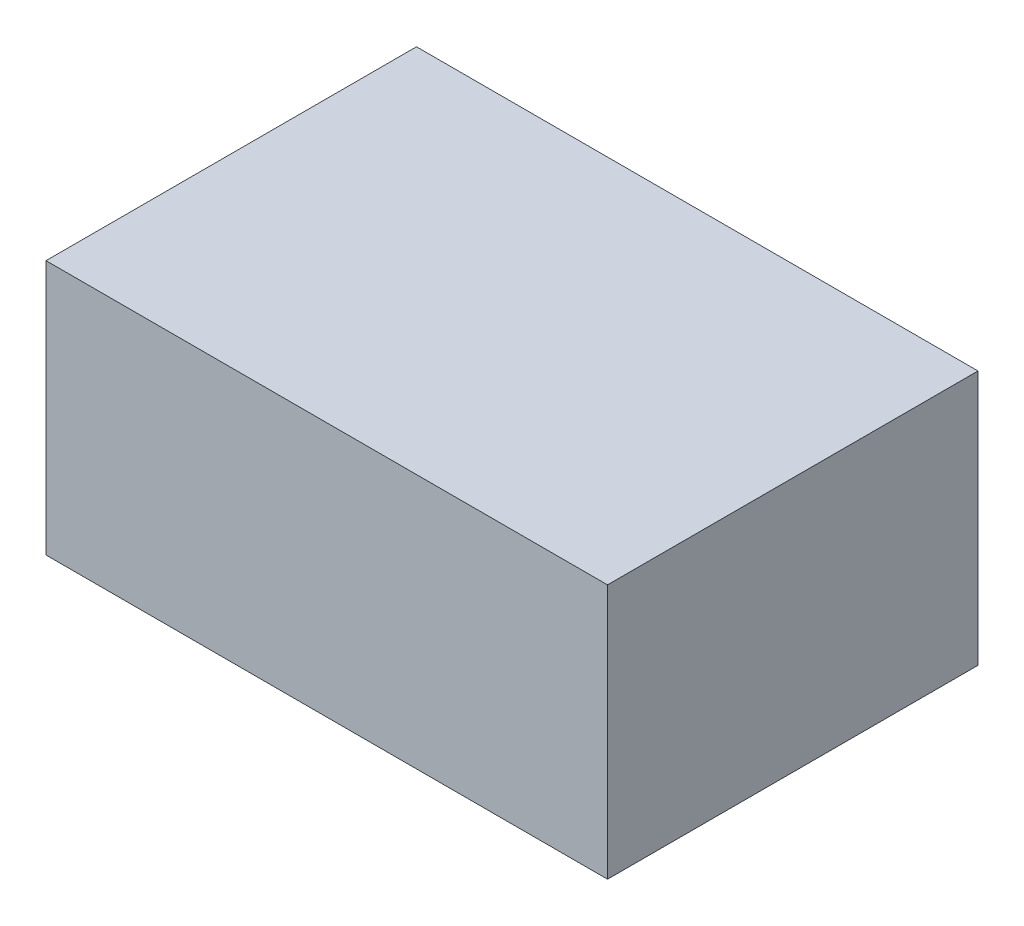
SolidWorks part; units mm, degrees
ref_plane "Front Plane" through (0, 0, 0) normal (0, 0, 1) x (1, 0, 0)
ref_plane "Top Plane" through (0, 0, 0) normal (0, 1, 0) x (1, 0, 0)
ref_plane "Right Plane" through (0, 0, 0) normal (1, 0, 0) x (0, 0, -1)
sketch "Sketch1" plane through (0, 94.8439, 0) normal (0, -1, 0) x (1, 0, 0)
  line L0 (462.1825, -188.3959) -> (474.7825, -157.5959) construction
  line L1 (474.7825, -157.5959) -> (474.7825, -189.4402) construction
  line L2 (474.7825, -189.4402) -> (462.1825, -157.5959) construction
  line L3 (468.4825, -188.3959) -> (468.4825, -157.5959) construction
  line L8 (443.5182, -157.3077) -> (493.7134, -189.5034) construction
  line L9 (443.7134, -189.5034) -> (493.5093, -156.6937) construction
  line L10 (474.7825, -188.3959) -> (462.1825, -188.3959) construction
  line L11 (462.1825, -157.5959) -> (474.7825, -157.5959) construction
  line L13 (443.4825, -153.1828) -> (493.4825, -153.1828)
  line L14 (443.4825, -153.1828) -> (443.4825, -186.171)
  line L15 (443.4825, -186.171) -> (493.4825, -186.171)
  line L16 (493.4825, -153.1828) -> (493.4825, -186.171)
  line L17 (443.4825, -153.1828) -> (493.4825, -186.171) construction
  line L18 (443.4825, -186.171) -> (493.4825, -153.1828) construction
  point P4 (468.3774, -173.2527)
  point P19 (468.4825, -169.6769)
  dimension "D1" = 50
  dimension "D2" = 32.9882
extrude "Boss-Extrude1" add sketch "Sketch1" along normal blind 22.7
